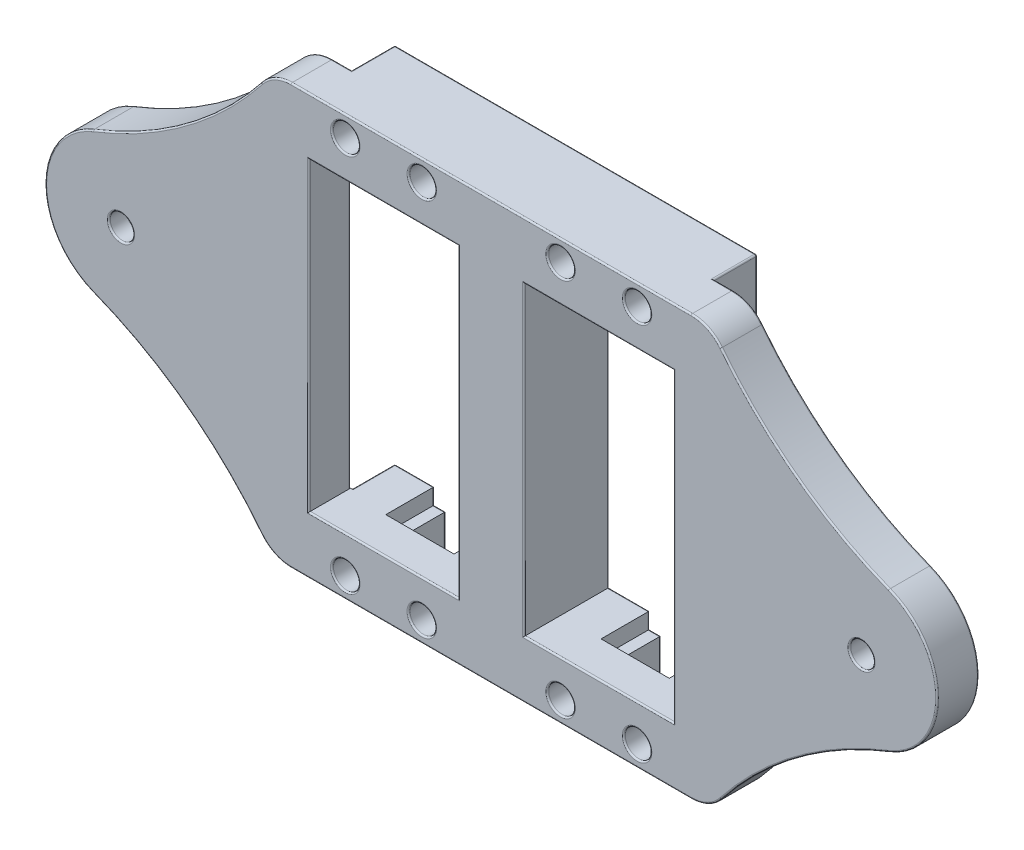
SolidWorks part; units mm, degrees
ref_plane "정면" through (0, 0, 0) normal (0, 0, 1) x (1, 0, 0)
ref_plane "윗면" through (0, 0, 0) normal (0, 1, 0) x (1, 0, 0)
ref_plane "우측면" through (0, 0, 0) normal (1, 0, 0) x (0, 0, -1)
sketch "스케치1" plane through (0, 0, 0) normal (0, 0, 1) x (1, 0, 0)
  line L0 (0, 0) -> (37.5737, 0) construction
  line L1 (4.5, -20) -> (4.5, 20)
  line L2 (4.5, 20) -> (23.9, 20)
  line L3 (4.5, -20) -> (23.9, -20)
  line L4 (23.9, 20) -> (23.9, 27.7)
  line L5 (23.9, -20) -> (23.9, -27.7)
  line L6 (23.9, 27.7) -> (-23.9, 27.7)
  line L7 (23.9, -27.7) -> (-23.9, -27.7)
  line L8 (0, -34.9912) -> (0, 34.9912) construction
  line L9 (-23.9, -20) -> (-23.9, -27.7)
  line L10 (-4.5, -20) -> (-23.9, -20)
  line L11 (-23.9, 20) -> (-23.9, 27.7)
  line L12 (-4.5, 20) -> (-23.9, 20)
  line L13 (-4.5, -20) -> (-4.5, 20)
  circle A0 centre (19.25, 25) radius 1.1
  circle A1 centre (19.25, -25) radius 1.1
  circle A2 centre (9.15, 25) radius 1.1
  circle A3 centre (9.15, -25) radius 1.1
  circle A4 centre (-9.15, -25) radius 1.1
  circle A5 centre (-19.25, -25) radius 1.1
  circle A6 centre (-19.25, 25) radius 1.1
  circle A7 centre (-9.15, 25) radius 1.1
  point P6 (4.5, 0)
  point P29 (0, -27.7)
  point P37 (0, 27.7)
  dimension "D5" = 2.2
  dimension "D7" = 4.65
  dimension "D8" = 10.1
  dimension "D1" = 40
  dimension "D2" = 19.4
  dimension "D3" = 4.5
  dimension "D4" = 7.7
  dimension "D6" = 2.7
extrude "보스-돌출1" add sketch "스케치1" along normal blind 5.7 contours L13 L10 L9 L7 L5 L3 L1 L2 L4 L6 L11 L12 A6 A5 A4 A1 A0 A2 A3 A7
sketch "스케치2" plane through (0, 0, 5.7) normal (0, 0, 1) x (1, 0, 0)
  line L0 (19.25, -25) -> (9.15, -25) construction
  line L1 (14.2, -25) -> (14.2, 33.3794) construction
  line L2 (23.9, -27.7) -> (26.3991, -27.7)
  line L3 (4.5, 0) -> (84.5955, 0) construction
  line L4 (4.5, -20) -> (4.5, 20) construction
  line L5 (23.9, 27.7) -> (26.3991, 27.7)
  line L6 (-23.9, -27.7) -> (-26.3991, -27.7)
  line L7 (23.9, 27.7) -> (23.9, -20)
  line L8 (0, 0) -> (0, 40.7303) construction
  line L9 (-23.9, 27.7) -> (-26.3991, 27.7)
  line L11 (-23.9, 20) -> (-23.9, -20)
  line L17 (-4.5, 20) -> (-4.5, -20)
  line L18 (-4.5, -20) -> (-23.9, -20)
  line L19 (-23.9, -20) -> (-23.9, -27.7)
  line L20 (-23.9, -27.7) -> (23.9, -27.7)
  line L21 (23.9, -27.7) -> (23.9, -20)
  line L22 (23.9, -20) -> (4.5, -20)
  line L23 (4.5, -20) -> (4.5, 20)
  line L24 (4.5, 20) -> (23.9, 20)
  line L25 (23.9, 20) -> (23.9, 27.7)
  line L26 (23.9, 27.7) -> (-23.9, 27.7)
  line L27 (-23.9, 27.7) -> (-23.9, 20)
  line L28 (-23.9, 20) -> (-4.5, 20)
  line L29 (-4.5, 20) -> (-4.5, -20)
  line L30 (-4.5, -20) -> (-23.9, -20)
  line L31 (-23.9, -20) -> (-23.9, -27.7)
  line L32 (-23.9, -27.7) -> (23.9, -27.7)
  line L33 (23.9, -27.7) -> (23.9, -20)
  line L34 (23.9, -20) -> (4.5, -20)
  line L35 (4.5, -20) -> (4.5, 20)
  line L36 (4.5, 20) -> (23.9, 20)
  line L37 (23.9, 20) -> (23.9, 27.7)
  line L38 (23.9, 27.7) -> (-23.9, 27.7)
  line L39 (-23.9, 27.7) -> (-23.9, 20)
  line L40 (-23.9, 20) -> (-4.5, 20)
  circle A0 centre (14.2, -10.12) radius 9 construction
  circle A1 centre (48.8525, 0) radius 27 construction
  circle A2 centre (19.25, -25) radius 1.1 construction
  circle A3 centre (9.15, -25) radius 1.1 construction
  circle A4 centre (-9.15, -25) radius 1.1 construction
  circle A5 centre (-19.25, -25) radius 1.1 construction
  circle A6 centre (19.25, 25) radius 1.1 construction
  circle A7 centre (9.15, 25) radius 1.1 construction
  circle A8 centre (-9.15, 25) radius 1.1 construction
  circle A9 centre (-19.25, 25) radius 1.1 construction
  circle A10 centre (19.25, -25) radius 1.1
  circle A11 centre (9.15, -25) radius 1.1
  circle A12 centre (-9.15, -25) radius 1.1
  circle A13 centre (-19.25, -25) radius 1.1
  circle A14 centre (19.25, 25) radius 1.1
  circle A15 centre (9.15, 25) radius 1.1
  circle A16 centre (-9.15, 25) radius 1.1
  circle A17 centre (-19.25, 25) radius 1.1
  circle A18 centre (48.8525, 0) radius 1.6
  arc A19 (52.497, -9.3122) -> (52.497, 9.3122) centre (48.8525, 0) ccw
  circle A21 centre (-48.8525, 0) radius 1.6
  arc A22 (52.497, -9.3122) -> (30.3323, -25.7871) centre (71.6307, -58.2014) ccw
  arc A23 (52.497, 9.3122) -> (30.3323, 25.7871) centre (71.6307, 58.2014) cw
  arc A24 (26.3991, -27.7) -> (30.3323, -25.7871) centre (26.3991, -22.7) ccw
  arc A25 (30.3323, 25.7871) -> (26.3991, 27.7) centre (26.3991, 22.7) ccw
  arc A26 (-26.3991, -27.7) -> (-30.3323, -25.7871) centre (-26.3991, -22.7) cw
  arc A27 (-52.497, -9.3122) -> (-30.3323, -25.7871) centre (-71.6307, -58.2014) cw
  arc A28 (-52.497, -9.3122) -> (-52.497, 9.3122) centre (-48.8525, 0) cw
  arc A29 (-52.497, 9.3122) -> (-30.3323, 25.7871) centre (-71.6307, 58.2014) ccw
  arc A30 (-30.3323, 25.7871) -> (-26.3991, 27.7) centre (-26.3991, 22.7) cw
  point P61 (72.2336, -74.3226)
  point P62 (77.7802, -55.4025)
  point P63 (0, 0)
  point P67 (28.9, -27.7)
  point P70 (28.9, 27.7)
  dimension "D2" = 18
  dimension "D3" = 54
  dimension "D6" = 3.2
  dimension "D7" = 20
  dimension "D8" = 5
  dimension "D9" = 105
  dimension "D10" = 5
  dimension "D1" = 14.88
  dimension "D4" = 36.1
  dimension "D5" = 0
extrude "보스-돌출2" add sketch "스케치2" along normal blind 5.5
sketch "스케치3" plane through (0, 0, 0) normal (0, 0, -1) x (-1, 0, 0)
  line L0 (0, 0) -> (0, -47.5313) construction
  line L1 (-14.2, -20) -> (-14.2, -34.0423) construction
  line L2 (-4.5, -20) -> (-23.9, -20) construction
  line L3 (14.2, -20) -> (14.2, -34.0423) construction
  line L4 (-18.7, -17.75) -> (-9.7, -17.75)
  line L5 (-18.7, -17.75) -> (-18.7, -22.25)
  line L6 (-9.7, -17.75) -> (-9.7, -22.25)
  line L7 (-18.7, -22.25) -> (-9.7, -22.25)
  line L8 (-18.7, -17.75) -> (-9.7, -22.25) construction
  line L9 (-9.7, -17.75) -> (-18.7, -22.25) construction
  line L10 (18.7, -17.75) -> (9.7, -22.25) construction
  line L11 (9.7, -17.75) -> (18.7, -22.25) construction
  line L12 (18.7, -17.75) -> (9.7, -17.75)
  line L13 (18.7, -17.75) -> (18.7, -22.25)
  line L14 (18.7, -22.25) -> (9.7, -22.25)
  line L15 (9.7, -17.75) -> (9.7, -22.25)
  line L16 (-17.2, -22.25) -> (-11.2, -22.25)
  line L17 (-17.2, -22.25) -> (-17.2, -31.2151)
  line L18 (-11.2, -22.25) -> (-11.2, -31.2151)
  line L19 (-17.2, -31.2151) -> (-11.2, -31.2151)
  line L20 (17.2, -22.25) -> (17.2, -31.2151)
  line L21 (17.2, -31.2151) -> (11.2, -31.2151)
  line L22 (11.2, -22.25) -> (11.2, -31.2151)
  point P20 (14.2, -20)
  line M23 (-4.5, -20) -> (-23.9, -20)
  line M25 (-23.9, -27.7) -> (23.9, -27.7)
  line M27 (23.9, -20) -> (4.5, -20)
  dimension "D1" = 9
  dimension "D2" = 4.5
  dimension "D3" = 6
  dimension "D4" = 3
extrude "컷-돌출1" cut sketch "스케치3" against normal blind 6.4 contours L5 L7 L6 M23 | L18 L7 L17 M25 | L14 L22 L20 M25 | L15 L14 L13 M27
sketch "스케치4" plane through (0, 0, 5.7) normal (0, 0, -1) x (-1, 0, 0)
  line L0 (0, 0) -> (0, 35.958) construction
  line L2 (-48.8525, -3.18) -> (-46.0985, -1.59)
  line L3 (48.8525, -3.18) -> (46.0985, -1.59)
  line L4 (-46.0985, -1.59) -> (-46.0985, 1.59)
  line L5 (46.0985, -1.59) -> (46.0985, 1.59)
  line L6 (-46.0985, 1.59) -> (-48.8525, 3.18)
  line L7 (46.0985, 1.59) -> (48.8525, 3.18)
  line L8 (-48.8525, 3.18) -> (-51.6065, 1.59)
  line L9 (48.8525, 3.18) -> (51.6065, 1.59)
  line L10 (-51.6065, 1.59) -> (-51.6065, -1.59)
  line L11 (51.6065, 1.59) -> (51.6065, -1.59)
  line L12 (-51.6065, -1.59) -> (-48.8525, -3.18)
  line L13 (51.6065, -1.59) -> (48.8525, -3.18)
  circle A0 centre (-48.8525, 0) radius 2.754 construction
  dimension "D1" = 3.18
extrude "컷-돌출2" cut sketch "스케치4" against normal blind 3
sketch "스케치5" plane through (0, 0, 11.2) normal (0, 0, 1) x (1, 0, 0)
  circle A0 centre (-19.25, 25) radius 1.75
  circle A1 centre (-9.15, 25) radius 1.75
  circle A2 centre (9.15, 25) radius 1.75
  circle A3 centre (19.25, 25) radius 1.75
  circle A4 centre (-19.25, -25) radius 1.75
  circle A5 centre (-9.15, -25) radius 1.75
  circle A6 centre (9.15, -25) radius 1.75
  circle A7 centre (19.25, -25) radius 1.75
  dimension "D1" = 3.5
extrude "컷-돌출3" cut sketch "스케치5" against normal blind 3
sketch "스케치6" plane through (0, 0, 11.2) normal (0, 0, 1) x (1, 0, 0)
  line L0 (4.5, 20) -> (23.9, 20) construction
  line L1 (4.5, -20) -> (4.5, 20) construction
  line L2 (23.9, -20) -> (23.9, 20) construction
  line L3 (23.9, -20) -> (4.5, -20) construction
  line L4 (-4.5, -20) -> (-23.9, -20) construction
  line L5 (-23.9, 20) -> (-23.9, -20) construction
  line L6 (-4.5, 20) -> (-4.5, -20) construction
  line L7 (-23.9, 20) -> (-4.5, 20) construction
  line L8 (4.5, 20) -> (23.9, 20)
  line L9 (4.5, -20) -> (4.5, 20)
  line L10 (23.9, -20) -> (23.9, 20)
  line L11 (23.9, -20) -> (4.5, -20)
  line L12 (-4.5, -20) -> (-23.9, -20)
  line L13 (-23.9, 20) -> (-23.9, -20)
  line L14 (-4.5, 20) -> (-4.5, -20)
  line L15 (-23.9, 20) -> (-4.5, 20)
  line L16 (-24.05, 20.15) -> (-4.35, 20.15)
  line L17 (-4.35, 20.15) -> (-4.35, -20.15)
  line L18 (-4.35, -20.15) -> (-24.05, -20.15)
  line L19 (-24.05, 20.15) -> (-24.05, -20.15)
  line L20 (4.35, 20.15) -> (24.05, 20.15)
  line L21 (24.05, -20.15) -> (24.05, 20.15)
  line L22 (24.05, -20.15) -> (4.35, -20.15)
  line L23 (4.35, -20.15) -> (4.35, 20.15)
  line M17 (23.9, 20) -> (23.9, -20)
  line M18 (23.9, -20) -> (4.5, -20)
  line M19 (4.5, -20) -> (4.5, 20)
  line M20 (4.5, 20) -> (23.9, 20)
  line M21 (-23.9, -20) -> (-23.9, 20)
  line M22 (-23.9, 20) -> (-4.5, 20)
  line M23 (-4.5, 20) -> (-4.5, -20)
  line M24 (-4.5, -20) -> (-23.9, -20)
  dimension "D1" = 0.15
  dimension "D2" = 0.15
extrude "컷-돌출4" cut sketch "스케치6" against normal through all contours L16 L19 L18 L17 M24 M21 M22 M23 | L23 L22 L21 L20 M20 M17 M18 M19
fillet "필렛1" radius 0.2 112 edges at (-25.1495, 27.7, 5.7) (-28.5859, 27.1964, 5.7) (-40.3119, 16.0661, 5.7) (-58.8525, 0, 5.7) (-25.1495, -27.7, 5.7) (-28.5859, -27.1964, 5.7) (25.1495, -27.7, 5.7) (28.5859, -27.1964, 5.7) (40.3119, -16.0661, 5.7) (58.8525, 0, 5.7) (25.1495, 27.7, 5.7) (28.5859, 27.1964, 5.7) (-23.9, -23.925, 0) (-20.55, -27.7, 0) (-17.2, -24.975, 0) (-17.95, -22.25, 0) (-18.7, -21.2, 0) (-21.3, -20.15, 0) (18.7, -21.2, 0) (17.95, -22.25, 0) (17.2, -24.975, 0) (20.55, -27.7, 0) (23.9, -23.925, 0) (21.3, -20.15, 0) (-4.35, 0, 0) (-7.025, -20.15, 0) (-9.7, -21.2, 0) (-10.45, -22.25, 0) (-11.2, -24.975, 0) (0, -27.7, 0) (11.2, -24.975, 0) (10.45, -22.25, 0) (9.7, -21.2, 0) (7.025, -20.15, 0) (4.35, 0, 0) (14.125, 20.15, 0) (23.9, 23.925, 0) (0, 27.7, 0) (-23.9, 23.925, 0) (-14.125, 20.15, 0) (20.35, 25, 8.2) (20.35, 25, 0) (10.25, 25, 8.2) (10.25, 25, 0) (-8.05, 25, 8.2) (-8.05, 25, 0) (-18.15, 25, 8.2) (-18.15, 25, 0) (-8.05, -25, 8.2) (-8.05, -25, 0) (-18.15, -25, 8.2) (-18.15, -25, 0) (10.25, -25, 8.2) (10.25, -25, 0) (20.35, -25, 8.2) (20.35, -25, 0) (47.2525, 0, 8.7) (-47.2525, 0, 8.7) (-14.2, -20.15, 11.2) (-4.35, 0, 11.2) (-14.2, 20.15, 11.2) (-24.05, 0, 11.2) (50.4525, 0, 11.2) (-47.2525, 0, 11.2) (0, 27.7, 11.2) (28.5859, 27.1964, 11.2) (40.3119, 16.0661, 11.2) (58.8525, 0, 11.2) (40.3119, -16.0661, 11.2) (28.5859, -27.1964, 11.2) (0, -27.7, 11.2) (-28.5859, -27.1964, 11.2) (-40.3119, -16.0661, 11.2) (-58.8525, 0, 11.2) (-40.3119, 16.0661, 11.2) (-28.5859, 27.1964, 11.2) (-17.5, 25, 11.2) (21, -25, 11.2) (10.9, -25, 11.2) (-7.4, -25, 11.2) (-7.4, 25, 11.2) (10.9, 25, 11.2) (21, 25, 11.2) (-17.5, -25, 11.2) (24.05, 0, 11.2) (14.2, 20.15, 11.2) (4.35, 0, 11.2) (14.2, -20.15, 11.2) (-24.05, 0, 5.7) (24.05, 0, 5.7) (23.9, -27.7, 2.85) (23.9, -20.15, 2.85) (-23.9, -27.7, 2.85) (-23.9, -20.15, 2.85) (-23.9, 20.15, 2.85) (-23.9, 27.7, 2.85) (-40.3119, -16.0661, 5.7) (40.3119, 16.0661, 5.7) (23.9, 20.15, 2.85) (23.9, 27.7, 2.85) (47.4755, -2.385, 5.7) (50.2295, -2.385, 5.7) (51.6065, 0, 5.7) (50.2295, 2.385, 5.7) (46.0985, 0, 5.7) (47.4755, 2.385, 5.7) (-51.6065, 0, 5.7) (-50.2295, -2.385, 5.7) (-47.4755, -2.385, 5.7) (-46.0985, 0, 5.7) (-47.4755, 2.385, 5.7) (-50.2295, 2.385, 5.7)
